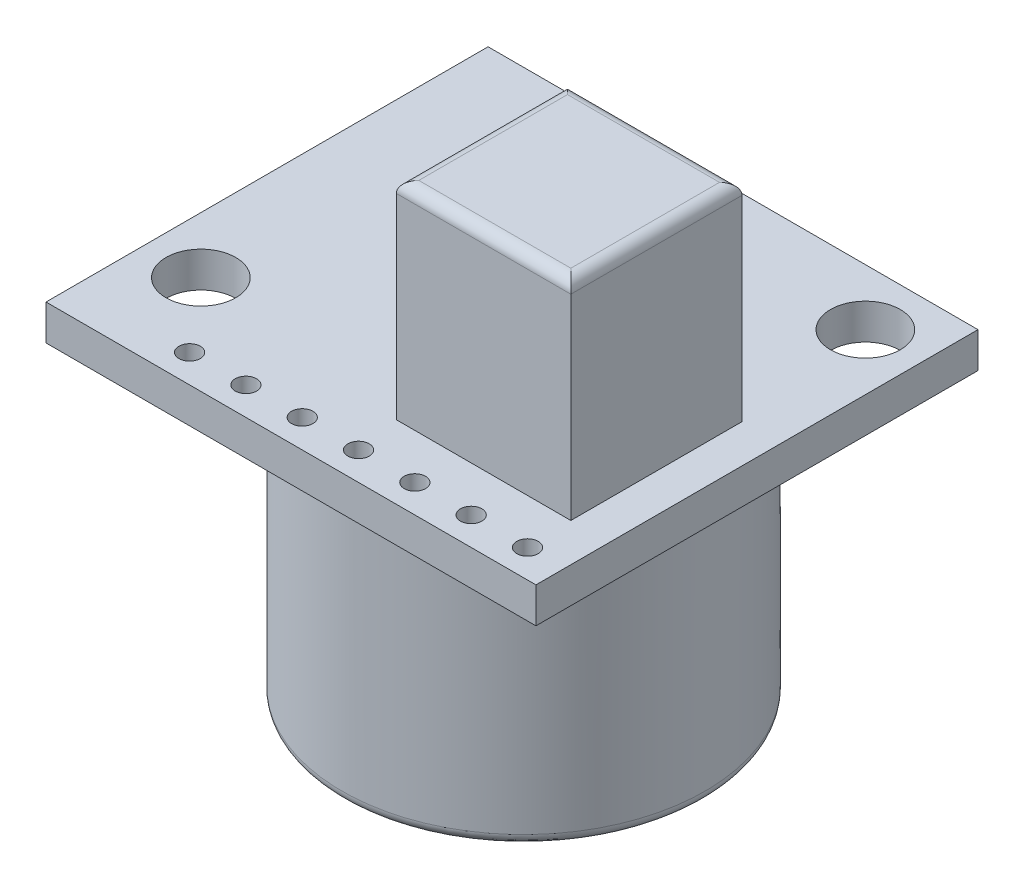
SolidWorks part; units mm, degrees
ref_plane "Front Plane" through (0, 0, 0) normal (0, 0, 1) x (1, 0, 0)
ref_plane "Top Plane" through (0, 0, 0) normal (0, 1, 0) x (1, 0, 0)
ref_plane "Right Plane" through (0, 0, 0) normal (1, 0, 0) x (0, 0, -1)
sketch "Sketch1" plane through (0, 0, 0) normal (0, 1, 0) x (1, 0, 0)
  line L1 (-11.049, 9.9695) -> (11.049, 9.9695)
  line L2 (-11.049, 9.9695) -> (-11.049, -9.9695)
  line L3 (-11.049, -9.9695) -> (11.049, -9.9695)
  line L4 (11.049, 9.9695) -> (11.049, -9.9695)
  circle A0 centre (8.509, 7.4295) radius 1.5748
  circle A1 centre (-8.509, -5.5245) radius 1.5748
  circle A2 centre (9.398, -8.6995) radius 0.4826
  circle A3 centre (6.858, -8.6995) radius 0.4826
  circle A4 centre (4.318, -8.6995) radius 0.4826
  circle A5 centre (1.778, -8.6995) radius 0.4826
  circle A6 centre (-0.762, -8.6995) radius 0.4826
  circle A7 centre (-3.302, -8.6995) radius 0.4826
  circle A8 centre (-5.842, -8.6995) radius 0.4826
  dimension "D3" = 2.54
  dimension "D7" = 1.651
  dimension "D1" = 19.939
  dimension "D2" = 22.098
  dimension "D4" = 2.54
  dimension "D5" = 17.018
  dimension "D6" = 15.494
  dimension "D8" = 18.669
  dimension "D9" = 7
extrude "Boss-Extrude1" add sketch "Sketch1" along normal blind 1.6002
sketch "Sketch2" plane through (0, 1.6002, 0) normal (0, 1, 0) x (1, 0, 0)
  line L0 (11.049, 9.9695) -> (-11.049, 9.9695) construction
  line L1 (1.4478, 1.0541) -> (9.3218, 1.0541)
  line L2 (1.4478, 1.0541) -> (1.4478, -6.6675)
  line L3 (1.4478, -6.6675) -> (9.3218, -6.6675)
  line L4 (9.3218, 1.0541) -> (9.3218, -6.6675)
  dimension "D1" = 7.7216
  dimension "D2" = 12.4968
  dimension "D3" = 8.9154
  dimension "D4" = 7.874
extrude "Boss-Extrude2" add sketch "Sketch2" along normal blind 9.3472
sketch "Sketch3" plane through (1.4478, 0, 0) normal (-1, 0, 0) x (0, 0, 1)
  line L1 (0.5915, 9.4713) -> (5.2816, 9.4713)
  line L2 (0.5915, 9.4713) -> (0.5915, 6.1544)
  line L3 (0.5915, 6.1544) -> (5.2816, 6.1544)
  line L4 (5.2816, 9.4713) -> (5.2816, 6.1544)
  line L5 (-0.2113, 5.6474) -> (0.9507, 5.6474)
  line L6 (-0.2113, 5.6474) -> (-0.2113, 4.9924)
  line L7 (-0.2113, 4.9924) -> (0.9507, 4.9924)
  line L8 (0.9507, 5.6474) -> (0.9507, 4.9924)
  line L9 (4.669, 5.6474) -> (5.7253, 5.6474)
  line L10 (4.669, 5.6474) -> (4.669, 4.9924)
  line L11 (4.669, 4.9924) -> (5.7253, 4.9924)
  line L12 (5.7253, 5.6474) -> (5.7253, 4.9924)
sketch "Sketch4" plane through (9.3218, 0, 0) normal (1, 0, 0) x (0, 0, -1)
  line L1 (-5.2816, 9.4713) -> (-0.5915, 9.4713)
  line L2 (-5.2816, 9.4713) -> (-5.2816, 6.1544)
  line L3 (-5.2816, 6.1544) -> (-0.5915, 6.1544)
  line L4 (-0.5915, 9.4713) -> (-0.5915, 6.1544)
  line L5 (-5.7253, 5.6474) -> (-4.669, 5.6474)
  line L6 (-5.7253, 5.6474) -> (-5.7253, 4.9924)
  line L7 (-5.7253, 4.9924) -> (-4.669, 4.9924)
  line L8 (-4.669, 5.6474) -> (-4.669, 4.9924)
  line L9 (-0.9507, 5.6474) -> (0.2113, 5.6474)
  line L10 (-0.9507, 5.6474) -> (-0.9507, 4.9924)
  line L11 (-0.9507, 4.9924) -> (0.2113, 4.9924)
  line L12 (0.2113, 5.6474) -> (0.2113, 4.9924)
sketch "Sketch5" plane through (0, 10.9474, 0) normal (0, 1, 0) x (1, 0, 0)
  circle A0 centre (5.5484, -2.6184) radius 3.2763
sketch "Sketch7" plane through (0, 0, 0) normal (0, -1, 0) x (1, 0, 0)
  line L0 (-11.049, 9.9695) -> (11.049, 9.9695) construction
  line L1 (11.049, 9.9695) -> (11.049, -9.9695) construction
  circle A0 centre (0, -0.5207) radius 8.1915
  dimension "D1" = 10.4902
  dimension "D2" = 11.049
extrude "Boss-Extrude6" add sketch "Sketch7" along normal blind 13.6398
sketch "Sketch8" plane through (0, 0, 0) normal (0, -1, 0) x (1, 0, 0)
  line L0 (-11.049, -9.9695) -> (-11.049, 9.9695) construction
  line L1 (-10.541, -7.9375) -> (-5.969, -7.9375)
  line L2 (-10.541, -7.9375) -> (-10.541, -1.3335)
  line L3 (-10.541, -1.3335) -> (-5.969, -1.3335)
  line L4 (-5.969, -7.9375) -> (-5.969, -1.3335)
  line L5 (11.049, -9.9695) -> (-11.049, -9.9695) construction
  dimension "D1" = 6.604
  dimension "D2" = 4.572
  dimension "D3" = 0.508
  dimension "D4" = 2.032
extrude "Boss-Extrude7" add sketch "Sketch8" along normal blind 2.032
fillet "Fillet2" radius 0.508 1 edges at (0, -13.6398, -8.7122)
fillet "Fillet3" radius 0.508 4 edges at (5.3848, 10.9474, -1.0541) (1.4478, 10.9474, 2.8067) (5.3848, 10.9474, 6.6675) (9.3218, 10.9474, 2.8067)
